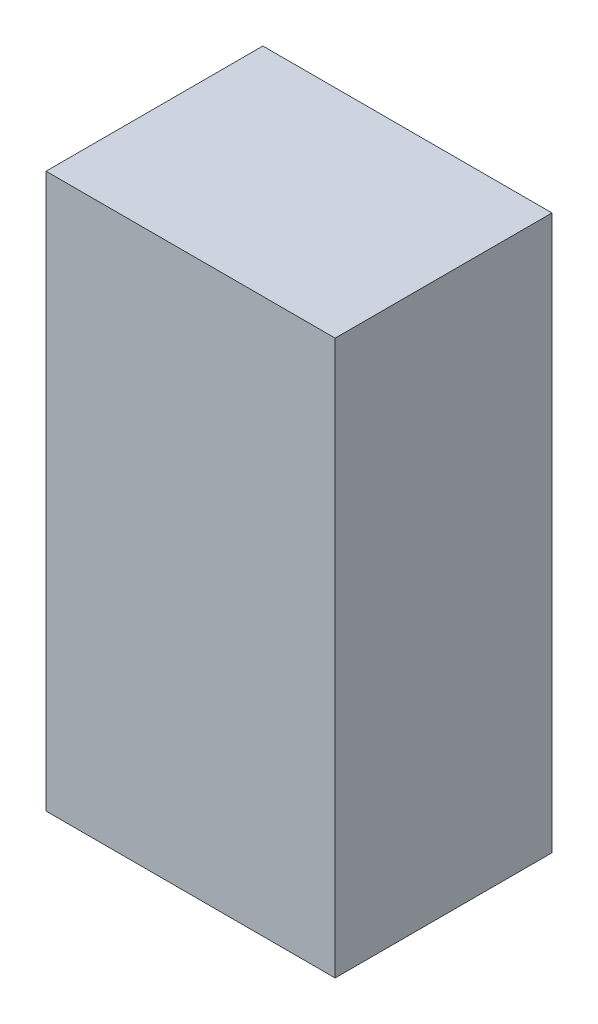
SolidWorks part; units mm, degrees
ref_plane "Front Plane" through (0, 0, 0) normal (0, 0, 1) x (1, 0, 0)
ref_plane "Top Plane" through (0, 0, 0) normal (0, 1, 0) x (1, 0, 0)
ref_plane "Right Plane" through (0, 0, 0) normal (1, 0, 0) x (0, 0, -1)
sketch "Sketch1" plane through (0, 0, 0) normal (0, 0, 1) x (1, 0, 0)
  line L1 (-30, 57.5) -> (30, 57.5)
  line L2 (-30, 57.5) -> (-30, -57.5)
  line L3 (-30, -57.5) -> (30, -57.5)
  line L4 (30, 57.5) -> (30, -57.5)
  line L5 (-30, 57.5) -> (30, -57.5) construction
  line L6 (-30, -57.5) -> (30, 57.5) construction
  point P0 (0, 0)
  dimension "D1" = 60
  dimension "D2" = 115
extrude "Boss-Extrude1" add sketch "Sketch1" along normal blind 45
